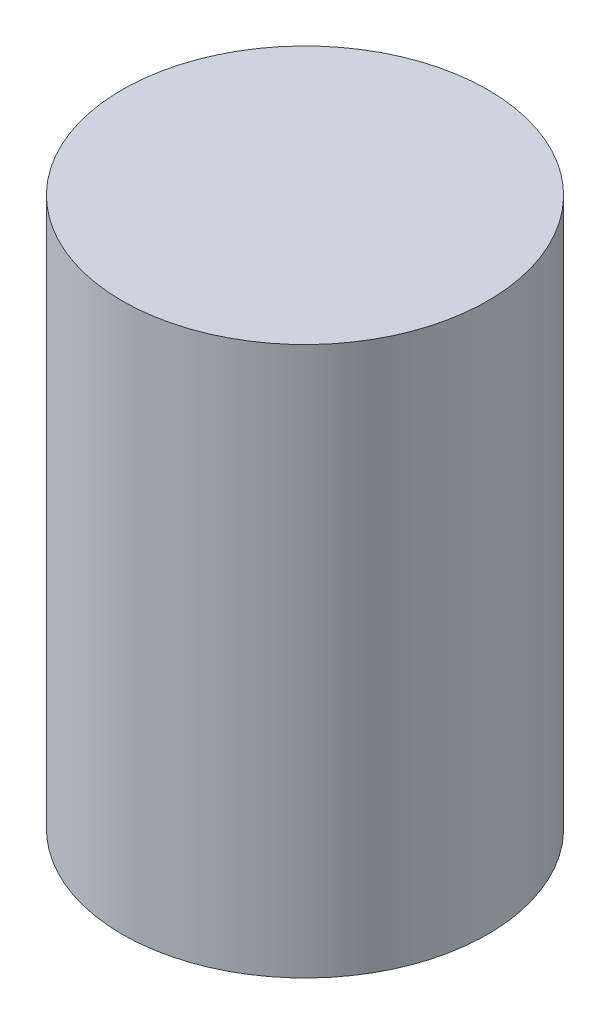
SolidWorks part; units mm, degrees
ref_plane "前视基准面" through (0, 0, 0) normal (0, 0, 1) x (1, 0, 0)
ref_plane "上视基准面" through (0, 0, 0) normal (0, 1, 0) x (1, 0, 0)
ref_plane "右视基准面" through (0, 0, 0) normal (1, 0, 0) x (0, 0, -1)
other "Configuration Table"
sketch "草图1" plane through (0, 0, 0) normal (0, 1, 0) x (1, 0, 0)
  circle A0 centre (0, 0) radius 10
  dimension "D1" = 20
extrude "凸台-拉伸1" add sketch "草图1" along normal blind 30
sketch "草图3" plane through (0, 0, 0) normal (1, 0, 0) x (0, 0, -1)
  line L0 (-10, 0) -> (10, 0) construction
  line L1 (-10, 30) -> (-10, 0) construction
  circle A0 centre (0, 7) radius 5
  dimension "D1" = 10
  dimension "D2" = 7
  dimension "D3" = 10
